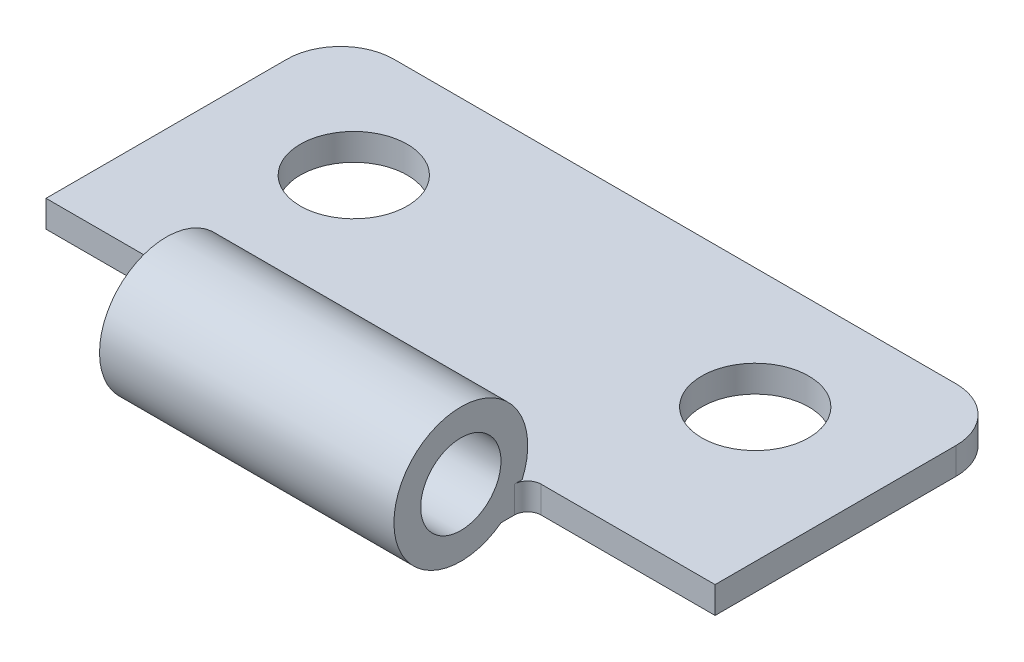
SolidWorks part; units mm, degrees
ref_plane "前视基准面" through (0, 0, 0) normal (0, 0, 1) x (1, 0, 0)
ref_plane "上视基准面" through (0, 0, 0) normal (0, 1, 0) x (1, 0, 0)
ref_plane "右视基准面" through (0, 0, 0) normal (1, 0, 0) x (0, 0, -1)
other "Configuration Table"
sketch "草图1" plane through (0, 0, 0) normal (0, 1, 0) x (1, 0, 0)
  line L0 (-12.5, 1) -> (-5.5, 1)
  line L1 (-12.5, 1) -> (-12.5, 12)
  line L2 (-12.5, 12) -> (12.5, 12)
  line L3 (12.5, 12) -> (12.5, 1)
  line L4 (-12.5, 7.5) -> (12.5, 7.5) construction
  line L5 (-5.5, 0) -> (5.5, 0)
  line L6 (5.5, 0) -> (5.5, 1)
  line L7 (-5.5, 0) -> (-5.5, 1)
  line L8 (5.5, 1) -> (12.5, 1)
  line L9 (0, 0) -> (0, 12) construction
  circle A0 centre (7.5, 7.5) radius 2
  circle A1 centre (-7.5, 7.5) radius 2
  dimension "D5" = 4
  dimension "D1" = 1
  dimension "D2" = 11
  dimension "D3" = 11
  dimension "D4" = 25
  dimension "D6" = 15
  dimension "D7" = 4.5
extrude "凸台-拉伸1" add sketch "草图1" along normal blind 1
fillet "圆角1" radius 2 2 edges at (-12.5, 0.5, -12) (12.5, 0.5, -12)
fillet "圆角2" radius 0.5 2 edges at (5.5, 0.5, -1) (-5.5, 0.5, -1)
sketch "草图3" plane through (0, 0, 0) normal (1, 0, 0) x (0, 0, -1)
  line L0 (1, 1) -> (1, 0) construction
  circle A0 centre (-1.5, 2) radius 2.5
  circle A1 centre (-1.5, 2) radius 1.5
  dimension "D1" = 5
  dimension "D2" = 3
  dimension "D3" = 2.5
extrude "凸台-拉伸2" add sketch "草图3" along normal mid plane 11
